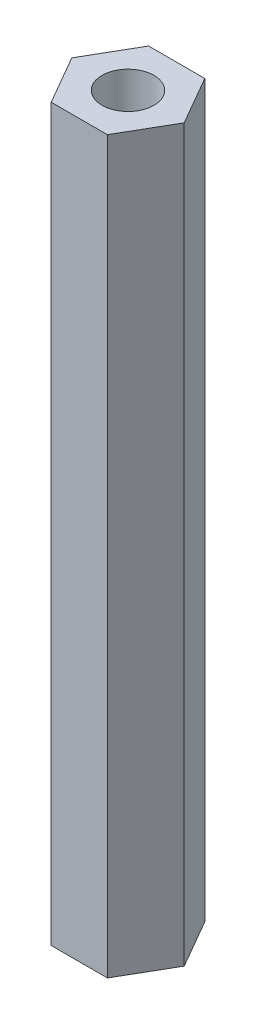
SolidWorks part; units mm, degrees
material "黄铜"
ref_plane "前视基准面" through (0, 0, 0) normal (0, 0, 1) x (1, 0, 0)
ref_plane "上视基准面" through (0, 0, 0) normal (0, 1, 0) x (1, 0, 0)
ref_plane "右视基准面" through (0, 0, 0) normal (1, 0, 0) x (0, 0, -1)
sketch "草图1" plane through (0, 0, 0) normal (0, 1, 0) x (1, 0, 0)
  line L1 (3.4641, 0) -> (1.7321, 3)
  line L2 (1.7321, 3) -> (-1.7321, 3)
  line L3 (-1.7321, 3) -> (-3.4641, 0)
  line L4 (-3.4641, 0) -> (-1.7321, -3)
  line L5 (-1.7321, -3) -> (1.7321, -3)
  line L6 (1.7321, -3) -> (3.4641, 0)
  circle A0 centre (0, 0) radius 3 construction
  circle A1 centre (0, 0) radius 1.6
  dimension "D1" = 6
  dimension "D2" = 3.2
extrude "凸台-拉伸1" add sketch "草图1" along normal blind 45
cosmetic thread "装饰螺纹线1" parameters "D2"=4
